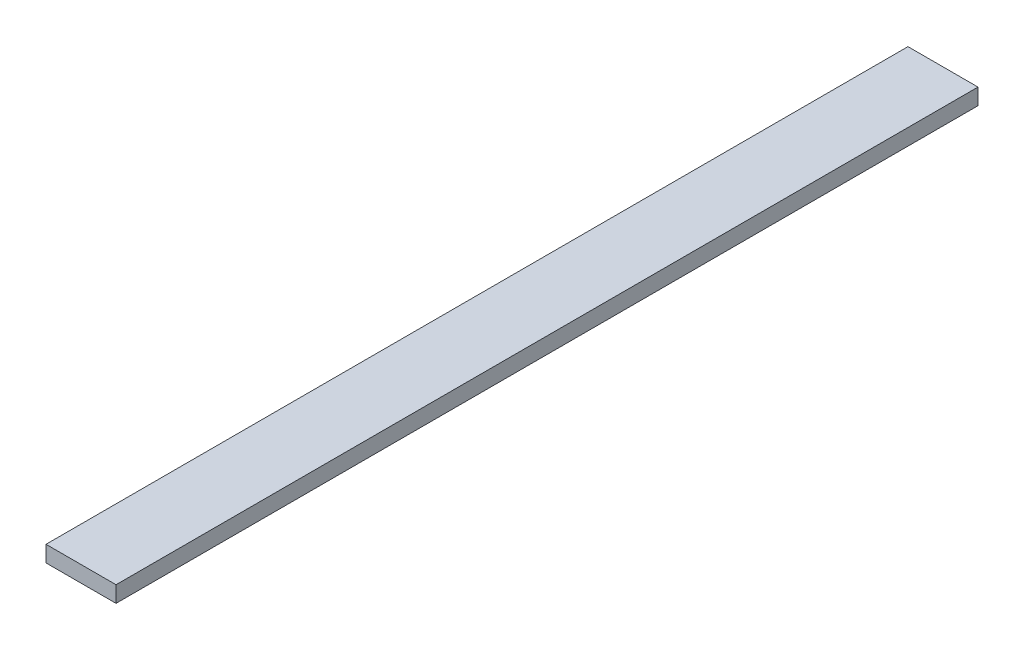
SolidWorks part; units mm, degrees
ref_plane "Front Plane" through (0, 0, 0) normal (0, 0, 1) x (1, 0, 0)
ref_plane "Top Plane" through (0, 0, 0) normal (0, 1, 0) x (1, 0, 0)
ref_plane "Right Plane" through (0, 0, 0) normal (1, 0, 0) x (0, 0, -1)
sketch "Sketch1" plane through (0, 0, 0) normal (0, 0, 1) x (1, 0, 0)
  line L1 (0, 0) -> (41.275, 0)
  line L2 (0, 0) -> (0, 9.525)
  line L3 (0, 9.525) -> (41.275, 9.525)
  line L4 (41.275, 0) -> (41.275, 9.525)
  dimension "D1" = 9.525
  dimension "D2" = 41.275
extrude "Boss-Extrude1" add sketch "Sketch1" along normal blind 508
